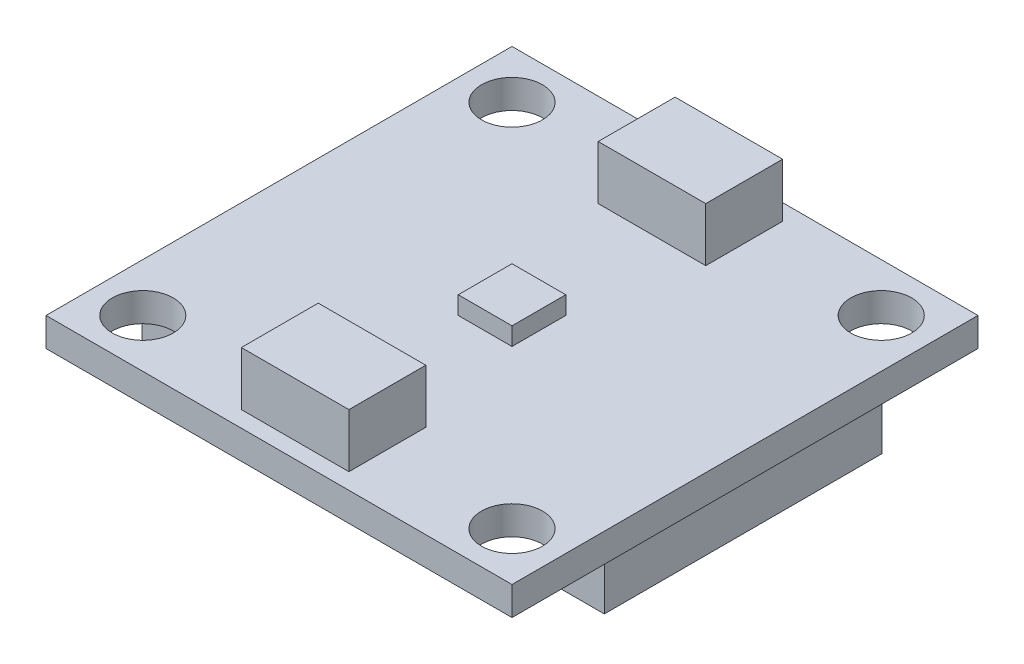
SolidWorks part; units mm, degrees
ref_plane "Front Plane" through (0, 0, 0) normal (0, 0, 1) x (1, 0, 0)
ref_plane "Top Plane" through (0, 0, 0) normal (0, 1, 0) x (1, 0, 0)
ref_plane "Right Plane" through (0, 0, 0) normal (1, 0, 0) x (0, 0, -1)
sketch "Sketch1" plane through (0, 0, 0) normal (0, 1, 0) x (1, 0, 0)
  line L0 (-12, 12) -> (-12, -12) construction
  line L1 (-13, 13) -> (13, 13)
  line L2 (-13, 13) -> (-13, -13)
  line L3 (-13, -13) -> (13, -13)
  line L4 (13, 13) -> (13, -13)
  line L5 (-13, 13) -> (13, -13) construction
  line L6 (-13, -13) -> (13, 13) construction
  line L11 (-12, -12) -> (12, -12) construction
  line L12 (12, 12) -> (12, -12) construction
  line L13 (-12, 12) -> (12, 12) construction
  circle A0 centre (-10.3, 10.3) radius 1.7
  circle A1 centre (10.3, 10.3) radius 1.7
  circle A2 centre (-10.3, -10.3) radius 1.7
  circle A3 centre (10.3, -10.3) radius 1.7
  point P0 (0, 0)
  dimension "D3" = 3.4
  dimension "D1" = 26
  dimension "D2" = 1
extrude "Boss-Extrude1" add sketch "Sketch1" along normal blind 1.6
sketch "Sketch2" plane through (0, 1.6, 0) normal (0, 1, 0) x (1, 0, 0)
  line L0 (-13, 0) -> (13, 0) construction
  line L1 (-13, 13) -> (-13, -13) construction
  line L2 (13, 13) -> (-13, 13) construction
  line L3 (-3, 12.1) -> (3, 12.1)
  line L4 (-3, 12.1) -> (-3, 7.81)
  line L5 (-3, 7.81) -> (3, 7.81)
  line L6 (3, 12.1) -> (3, 7.81)
  line L7 (-3, -7.81) -> (3, -7.81)
  line L8 (3, -12.1) -> (3, -7.81)
  line L9 (-3, -12.1) -> (3, -12.1)
  line L10 (-3, -12.1) -> (-3, -7.81)
  point P2 (0, 0)
  point P4 (0, 7.81)
  dimension "D1" = 6
  dimension "D2" = 4.29
  dimension "D3" = 0.9
extrude "Boss-Extrude2" add sketch "Sketch2" along normal blind 3
sketch "Sketch3" plane through (0, 0, 0) normal (0, -1, 0) x (1, 0, 0)
  line L1 (-12.9, 7.75) -> (-10.4, 7.75)
  line L2 (-12.9, 7.75) -> (-12.9, -7.75)
  line L3 (-12.9, -7.75) -> (-10.4, -7.75)
  line L4 (-10.4, 7.75) -> (-10.4, -7.75)
  line L5 (10.4, 7.75) -> (12.9, 7.75)
  line L6 (10.4, 7.75) -> (10.4, -7.75)
  line L7 (10.4, -7.75) -> (12.9, -7.75)
  line L8 (12.9, 7.75) -> (12.9, -7.75)
  line L10 (-10.4, 0) -> (10.4, 0) construction
  line L11 (13, 13) -> (13, -13) construction
  point P8 (-10.4, 0)
  point P9 (10.4, 0)
  point P14 (0, 0)
  dimension "D1" = 15.5
  dimension "D2" = 2.5
  dimension "D3" = 0.1
extrude "Boss-Extrude3" add sketch "Sketch3" along normal blind 2.5
sketch "Sketch4" plane through (0, 1.6, 0) normal (0, 1, 0) x (1, 0, 0)
  line L1 (-1.5, 1.5) -> (1.5, 1.5)
  line L2 (-1.5, 1.5) -> (-1.5, -1.5)
  line L3 (-1.5, -1.5) -> (1.5, -1.5)
  line L4 (1.5, 1.5) -> (1.5, -1.5)
  line L5 (-1.5, 1.5) -> (1.5, -1.5) construction
  line L6 (-1.5, -1.5) -> (1.5, 1.5) construction
  point P0 (0, 0)
  dimension "D1" = 3
extrude "Boss-Extrude4" add sketch "Sketch4" along normal blind 1
